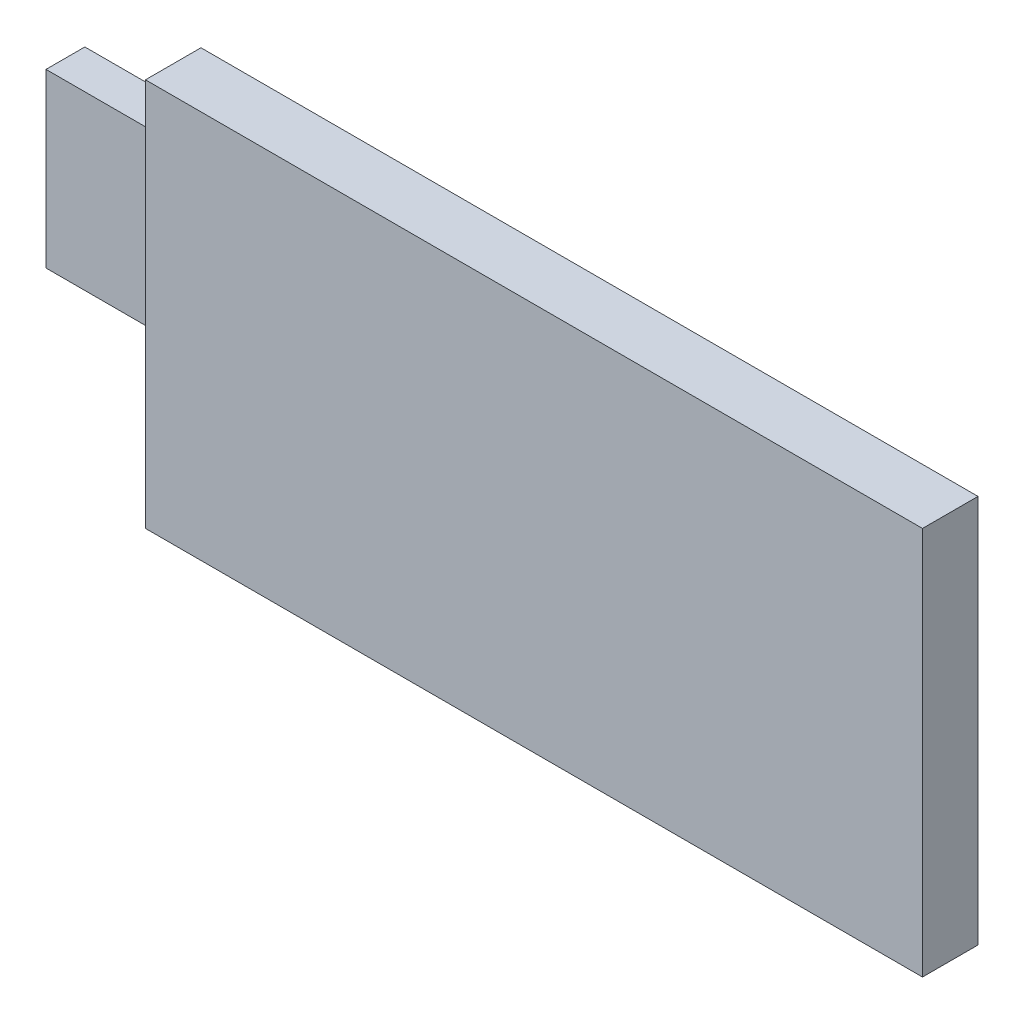
SolidWorks part; units mm, degrees
ref_plane "Front Plane" through (0, 0, 0) normal (0, 0, 1) x (1, 0, 0)
ref_plane "Top Plane" through (0, 0, 0) normal (0, 1, 0) x (1, 0, 0)
ref_plane "Right Plane" through (0, 0, 0) normal (1, 0, 0) x (0, 0, -1)
sketch "Sketch1" plane through (0, 0, 0) normal (0, 0, 1) x (1, 0, 0)
  line L1 (-17.78, -8.89) -> (17.78, -8.89)
  line L2 (-17.78, -8.89) -> (-17.78, 8.89)
  line L3 (-17.78, 8.89) -> (17.78, 8.89)
  line L4 (17.78, -8.89) -> (17.78, 8.89)
  line L5 (-17.78, -8.89) -> (17.78, 8.89) construction
  line L6 (-17.78, 8.89) -> (17.78, -8.89) construction
  point P0 (0, 0)
  dimension "D1" = 17.78
  dimension "D2" = 35.56
extrude "Boss-Extrude1" add sketch "Sketch1" along normal blind 2.54
sketch "Sketch2" plane through (0, 0, 0) normal (0, 0, 1) x (1, 0, 0)
  line L1 (-23.0932, 6.2656) -> (-17.2512, 6.2656)
  line L2 (-23.0932, 6.2656) -> (-23.0932, -1.6084)
  line L3 (-23.0932, -1.6084) -> (-17.2512, -1.6084)
  line L4 (-17.2512, 6.2656) -> (-17.2512, -1.6084)
  line L5 (-23.0932, 6.2656) -> (-17.2512, -1.6084) construction
  line L6 (-23.0932, -1.6084) -> (-17.2512, 6.2656) construction
  point P0 (-20.1722, 2.3286)
  dimension "D1" = 7.874
  dimension "D2" = 5.842
extrude "Boss-Extrude2" add sketch "Sketch2" along normal blind 1.778
